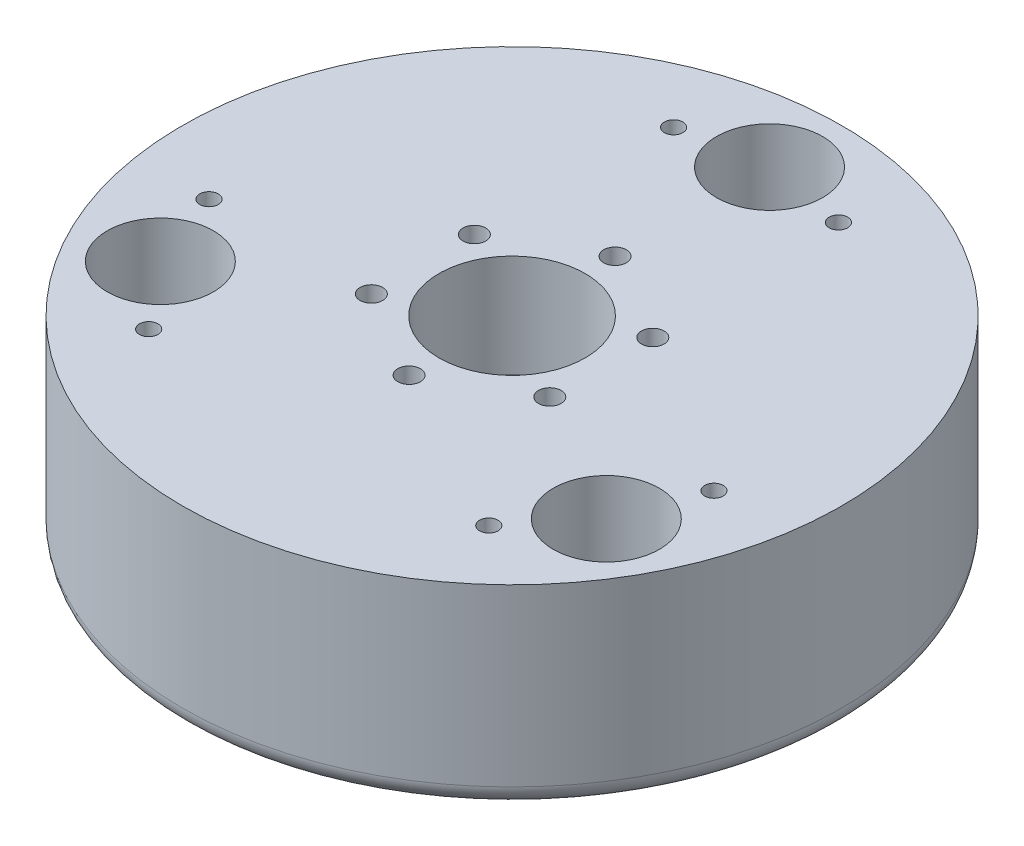
SolidWorks part; units mm, degrees
ref_plane "Спереди" through (0, 0, 0) normal (0, 0, 1) x (1, 0, 0)
ref_plane "Сверху" through (0, 0, 0) normal (0, 1, 0) x (1, 0, 0)
ref_plane "Справа" through (0, 0, 0) normal (1, 0, 0) x (0, 0, -1)
sketch "Эскиз1" plane through (0, 0, 0) normal (0, 1, 0) x (1, 0, 0)
  circle A3 centre (0, 0) radius 32
  circle A4 centre (0, 0) radius 4
  circle A6 centre (0, 0) radius 25 construction
  circle A7 centre (0, 25) radius 3
  circle A8 centre (21.6506, -12.5) radius 3
  circle A9 centre (-21.6506, -12.5) radius 3
  dimension "D4" = 64
  dimension "D1" = 8
  dimension "D2" = 50
  dimension "D3" = 6
  dimension "D5" = 3
extrude "Бобышка-Вытянуть1" add sketch "Эскиз1" along normal blind 19
fillet "Скругление1" radius 2 1 edges at (0, 0, 32)
sketch "Эскиз2" plane through (0, 19, 0) normal (0, 1, 0) x (1, 0, 0)
  circle A0 centre (0, 25) radius 5.15
  circle A2 centre (21.6506, -12.5) radius 5.15
  circle A3 centre (-21.6506, -12.5) radius 5.15
  circle A4 centre (-21.6506, -12.5) radius 3 construction
  dimension "D1" = 10.3
  dimension "D2" = 3
extrude "Вырез-Вытянуть1" cut sketch "Эскиз2" against normal blind 15.2
sketch "Эскиз3" plane through (0, 0, 0) normal (0, -1, 0) x (1, 0, 0)
  circle A0 centre (0, 0) radius 25 construction
  circle A1 centre (0, 25) radius 2.55
  circle A2 centre (21.6506, -12.5) radius 2.55
  circle A3 centre (-21.6506, -12.5) radius 2.55
  dimension "D2" = 3
  dimension "D1" = 5.1
extrude "Вырез-Вытянуть2" cut sketch "Эскиз3" against normal blind 15
sketch "Эскиз4" plane through (0, 19, 0) normal (0, 1, 0) x (1, 0, 0)
  circle A0 centre (0, 0) radius 10 construction
  circle A1 centre (0, 10) radius 1.1
  circle A2 centre (8.6603, 5) radius 1.1
  circle A3 centre (8.6603, -5) radius 1.1
  circle A4 centre (0, -10) radius 1.1
  circle A5 centre (-8.6603, -5) radius 1.1
  circle A6 centre (-8.6603, 5) radius 1.1
  dimension "D3" = 6
  dimension "D1" = 20
  dimension "D2" = 2.2
extrude "Вырез-Вытянуть3" cut sketch "Эскиз4" against normal through all
sketch "Эскиз7" plane through (0, 0, 0) normal (0, -1, 0) x (1, 0, 0)
  circle A0 centre (0, 10) radius 1.8 construction
  circle A7 centre (8.6603, 5) radius 1.8
  circle A8 centre (8.6603, -5) radius 1.8 construction
  circle A9 centre (0, -10) radius 1.8
  circle A10 centre (-8.6603, -5) radius 1.8 construction
  circle A11 centre (-8.6603, 5) radius 1.8
  circle A12 centre (8.6603, 5) radius 1.1 construction
  dimension "D1" = 3.6
  dimension "D2" = 6
extrude "Вырез-Вытянуть5" cut sketch "Эскиз7" against normal offset from surface (3 mm away) 16 up to face at (0, 19, -8.9)
chamfer "Фаска1" distance 1 angle 45 7 edges at (21.6506, 0, -15.05) (0, 0, -22) (-21.6506, 0, -15.05) (-21.6506, 0, 15.5) (0, 0, 22.45) (21.6506, 0, 15.5) (0, 0, 4)
sketch "Эскиз8" plane through (0, 19, 0) normal (0, 1, 0) x (1, 0, 0)
  circle A0 centre (0, 0) radius 7.1
  dimension "D1" = 14.2
extrude "Вырез-Вытянуть6" cut sketch "Эскиз8" against normal blind 10
sketch "Эскиз9" plane through (0, 19, 0) normal (0, 1, 0) x (1, 0, 0)
  line L0 (0, 0) -> (0, 25) construction
  line L1 (-8, 23.6854) -> (8, 23.6854) construction
  circle A0 centre (0, 0) radius 25 construction
  circle A1 centre (-8, 23.6854) radius 0.9
  circle A2 centre (8, 23.6854) radius 0.9
  circle A3 centre (16.5122, -18.7709) radius 0.9
  circle A4 centre (24.5122, -4.9145) radius 0.9
  circle A5 centre (-24.5122, -4.9145) radius 0.9
  circle A6 centre (-16.5122, -18.7709) radius 0.9
  dimension "D1" = 16
  dimension "D2" = 1.8
  dimension "D3" = 1.8
  dimension "D4" = 3
extrude "Вырез-Вытянуть7" cut sketch "Эскиз9" against normal through all
equation "\"motor_diameter\"= 30"
equation "\"mm_diameter\"= IIF ( \"motor_diameter\" < 34 , 41 , \"motor_diameter\" + 8 )"
equation "\"upper_shafts_diameter\"= 5"
equation "\"upper_shats_length\"= 180"
equation "\"upper_bearing_d1\"= 10"
equation "\"upper_bearing_d2\"= 5"
equation "\"upper_bearing_h\"= 15"
equation "\"lower_shafts_diameter\"= 5"
equation "\"lower_shafts_length\"= 180"
equation "\"lower_bearing_d1\"= 10"
equation "\"lower_bearing_d2\"= 5"
equation "\"lower_bearing_h\"= 15"
equation "\"print_offset\"= 0.2"
equation "\"bh_screws_d\"= 2"
equation "\"bh_screws_h\"= 20"
equation "\"bh_screws_hh_d\"= 3.4"
equation "\"bh_screws_hh_h\"= 2"
equation "\"bh_nut_d\"= 3.8"
equation "\"bh_nut_h\"= 2"
equation "\"motor_screws_d\"= 3"
equation "\"motor_screws_h\"= 16"
equation "\"motor_screws_hh_d\"= 5.5"
equation "\"motor_screws_hh_h\"= 3"
equation "\"plate_hole_distance\"= 25.4"
equation "\"plate_screws_d\"= 6.5"
equation "\"shafts_diameter\"= IIF ( \"mm_diameter\" < 42 , 42 + 8 , \"mm_diameter\" + 8 )"
equation "\"D4@Эскиз1\"= \"system_radius\" * 2"
equation "\"central_hole_diameter\"= 8"
equation "\"bh_thikness\"= 4"
equation "\"D1@Эскиз1\"=\"central_hole_diameter\""
equation "\"D2@Эскиз1\"=\"shafts_diameter\""
equation "\"D3@Эскиз1\" = \"lower_shafts_diameter\" + 1"
equation "\"D1@Бобышка-Вытянуть1\" = \"bh_thikness\" + \"lower_bearing_h\""
equation "\"D1@Эскиз2\" = \"lower_bearing_d1\" + \"print_offset\" * 1.5"
equation "\"D1@Вырез-Вытянуть1\" = \"lower_bearing_h\" + \"print_offset\""
equation "\"D1@Эскиз3\" = \"upper_shafts_diameter\" + \"print_offset\" / 2"
equation "\"D1@Вырез-Вытянуть2\"= \"upper_bearing_h\""
equation "\"D2@Эскиз4\"=\"bh_screws_d\"+\"print_offset\""
equation "\"D1@Вырез-Вытянуть5\"=\"bh_screws_h\"-\"bh_thikness\""
equation "\"D1@Эскиз7\"=\"bh_screws_hh_d\"+\"print_offset\""
equation "\"D1@Вырез-Вытянуть6\"=14-\"bh_thikness\""
equation "\"D2@Эскиз9\"=\"bh_screws_d\"-\"print_offset\""
equation "\"D3@Эскиз9\"=\"D2@Эскиз9\""
equation "\"ends_screws_d\"= 4"
equation "\"ends_screws_h\"= 16"
equation "\"ends_screws_hh_d\"= 6.7"
equation "\"ends_screws_hh_h\"= 4.1"
equation "\"ends_nut_d\"= 6.8"
equation "\"ends_nut_h\"= 3"
equation "\"system_radius\" = ( \"shafts_diameter\" + 12 + \"bh_thikness\" / 2 ) / 2"
equation "\"encoder_distance\"= \"system_radius\" + 4"
equation "\"tape_position\"= \"encoder_distance\" - 2 + 3.9 + 1.7 / 2"
equation "\"ft_sensor_d1\" = 9.8"
equation "\"ft_sensor_d2\"= 24.9"
equation "\"ft_sensor_h\"= 7"
equation "\"carbon_pipe_d\"= 14"
equation "\"D1@Эскиз8\"=\"print_offset\"+14.00мм"
